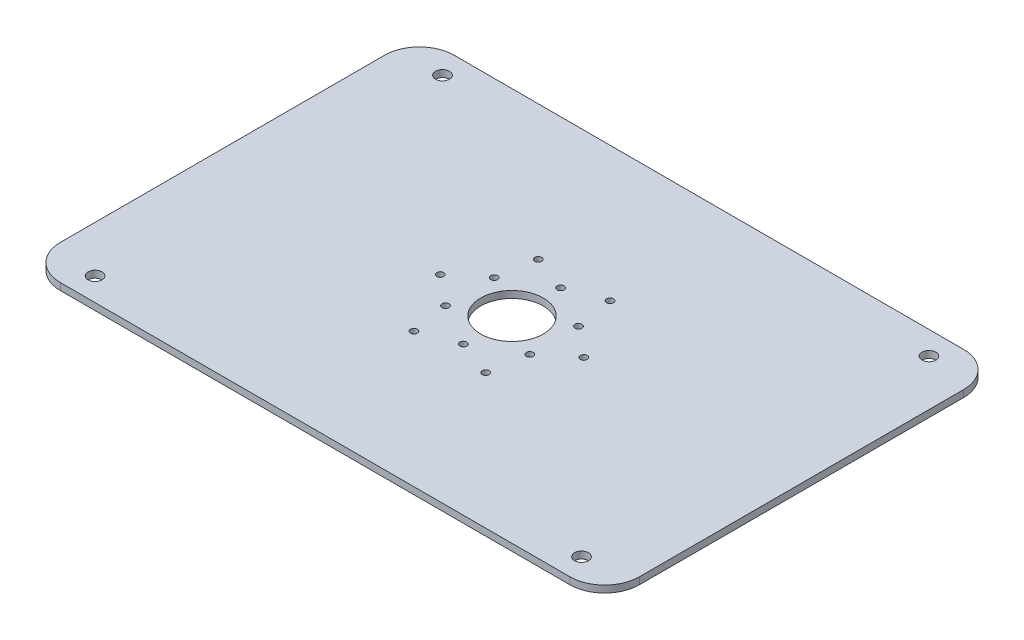
SolidWorks part; units mm, degrees
material "C-玻璃纤维"
ref_plane "前视基准面" through (0, 0, 0) normal (0, 0, 1) x (1, 0, 0)
ref_plane "上视基准面" through (0, 0, 0) normal (0, 1, 0) x (1, 0, 0)
ref_plane "右视基准面" through (0, 0, 0) normal (1, 0, 0) x (0, 0, -1)
other "Configuration Table"
sketch "草图1" plane through (0, 0, 0) normal (0, 1, 0) x (1, 0, 0)
  line L1 (-125, -85) -> (125, -85)
  line L2 (-125, -85) -> (-125, 85)
  line L3 (-125, 85) -> (125, 85)
  line L4 (125, -85) -> (125, 85)
  line L5 (0, 85) -> (0, -85) construction
  line L6 (-125, 0) -> (125, 0) construction
  circle A0 centre (-105, 75) radius 3
  circle A1 centre (105, 75) radius 3
  circle A2 centre (-105, -75) radius 3
  circle A3 centre (105, -75) radius 3
  dimension "D1" = 6
  dimension "D2" = 150
  dimension "D3" = 210
  dimension "D4" = 250
  dimension "D5" = 170
extrude "凸台-拉伸1" add sketch "草图1" along normal blind 3
fillet "圆角1" radius 15 4 edges at (125, 1.5, 85) (125, 1.5, -85) (-125, 1.5, -85) (-125, 1.5, 85)
sketch "草图2" plane through (0, 0, 0) normal (0, 1, 0) x (1, 0, 0)
  line L0 (-160.4139, 0) -> (155.4702, 0) construction
  line L1 (0, 98.9588) -> (0, -103.2206) construction
  line L2 (0, 0) -> (0, 21) construction
  line L3 (0, 0) -> (18.1865, 10.5) construction
  circle A5 centre (0, 0) radius 21 construction
  circle A6 centre (0, 21) radius 1.5
  circle A7 centre (18.1865, 10.5) radius 1.5
  circle A8 centre (18.1865, -10.5) radius 1.5
  circle A9 centre (0, -21) radius 1.5
  circle A10 centre (-18.1865, -10.5) radius 1.5
  circle A11 centre (-18.1865, 10.5) radius 1.5
  circle A12 centre (0, 0) radius 31 construction
  circle A13 centre (31, 0) radius 1.5
  circle A14 centre (15.5, -26.8468) radius 1.5
  circle A15 centre (-15.5, -26.8468) radius 1.5
  circle A16 centre (-31, 0) radius 1.5
  circle A17 centre (-15.5, 26.8468) radius 1.5
  circle A18 centre (15.5, 26.8468) radius 1.5
  circle A19 centre (0, 0) radius 13.5
  point P37 (0, 0)
  dimension "D2" = 3
  dimension "D1" = 42
  dimension "D3" = 6
  dimension "D5" = 62
  dimension "D6" = 3
  dimension "D8" = 27
  dimension "D4" = 60
  dimension "D7" = 6
extrude "切除-拉伸1" cut sketch "草图2" along normal through all
